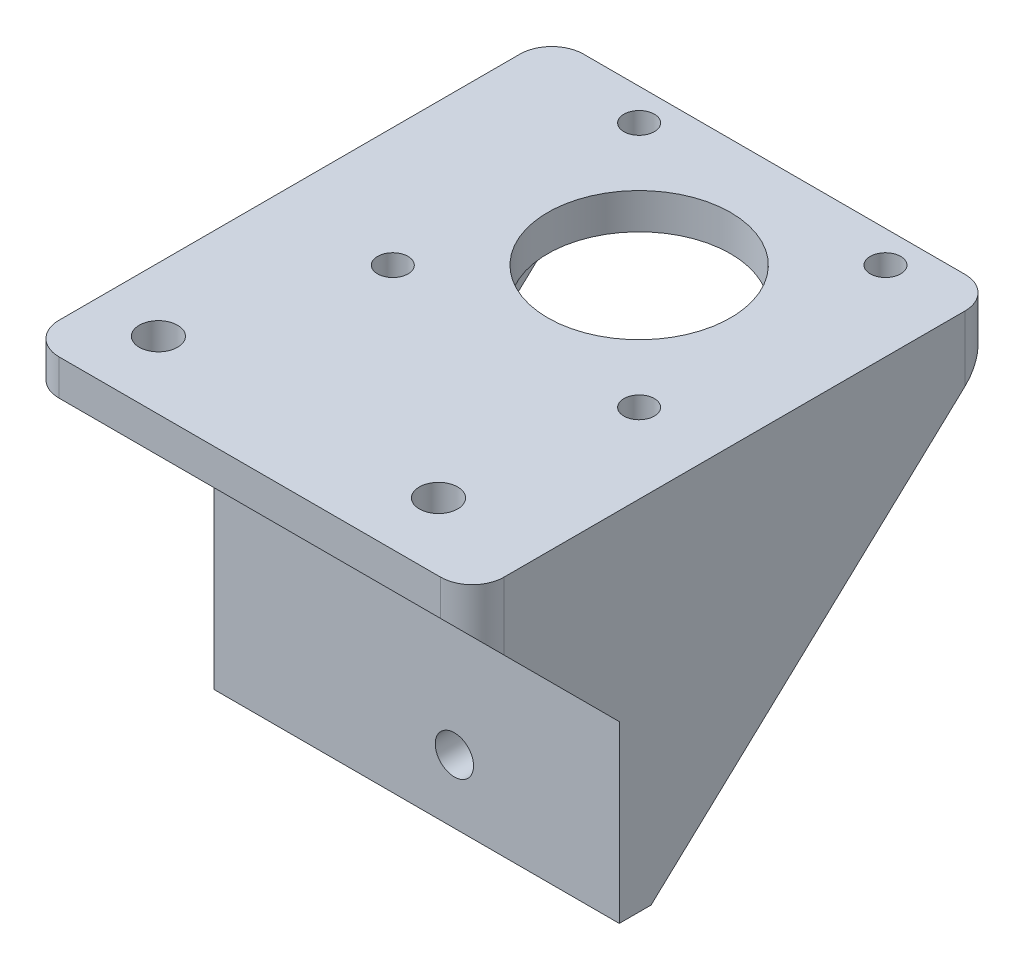
SolidWorks part; units mm, degrees
ref_plane "Front Plane" through (0, 0, 0) normal (0, 0, 1) x (1, 0, 0)
ref_plane "Top Plane" through (0, 0, 0) normal (0, 1, 0) x (1, 0, 0)
ref_plane "Right Plane" through (0, 0, 0) normal (1, 0, 0) x (0, 0, -1)
sketch "Sketch1" plane through (0, 0, 0) normal (0, 1, 0) x (1, 0, 0)
  line L0 (-15.5, 15.5) -> (15.5, -15.5) construction
  line L6 (15.5, 19.5) -> (-26.5, 19.5)
  line L7 (19.5, 15.5) -> (19.5, -42.5)
  line L8 (15.5, -46.5) -> (-26.5, -46.5)
  line L9 (-30.5, 15.5) -> (-30.5, -42.5)
  circle A0 centre (0, 0) radius 11.5
  circle A1 centre (15.5, 15.5) radius 1.9154
  circle A2 centre (-15.5, 15.5) radius 1.9154
  circle A3 centre (-15.5, -15.5) radius 1.9154
  circle A4 centre (15.5, -15.5) radius 1.9154
  arc A9 (-26.5, -46.5) -> (-30.5, -42.5) centre (-26.5, -42.5) cw
  arc A10 (19.5, -42.5) -> (15.5, -46.5) centre (15.5, -42.5) cw
  arc A11 (15.5, 19.5) -> (19.5, 15.5) centre (15.5, 15.5) cw
  arc A12 (-26.5, 19.5) -> (-30.5, 15.5) centre (-26.5, 15.5) ccw
  circle A13 centre (-22.5, -38) radius 2.41
  circle A14 centre (12.75, -38) radius 2.41
  point P15 (0, 0)
  point P37 (-30.5, -46.5)
  point P44 (-30.5, 19.5)
  dimension "D1" = 23
  dimension "D13" = 3.8309
  dimension "D14" = 4
  dimension "D10" = 4.82
  dimension "D2" = 31
  dimension "D3" = 31
  dimension "D4" = 50
  dimension "D5" = 66
  dimension "D6" = 4
  dimension "D7" = 4
  dimension "D8" = 8.5
  dimension "D9" = 8
  dimension "D11" = 6.75
extrude "Boss-Extrude1" add sketch "Sketch1" along normal blind 4.5
sketch "Sketch2" plane through (0, 0, 0) normal (0, 1, 0) x (1, 0, 0)
  line L0 (0, -2.475) -> (0, 2.475) construction
  line L1 (-21.5, -24) -> (21.5, -24)
  line L2 (-21.5, -24) -> (-21.5, 19)
  line L3 (-21.5, 19) -> (21.5, 19)
  line L4 (21.5, -24) -> (21.5, 19)
  line L5 (-21.5, -24) -> (21.5, 19) construction
  line L6 (-21.5, 19) -> (21.5, -24) construction
  line L7 (-25.5, -28) -> (25.5, -28)
  line L8 (-25.5, -28) -> (-25.5, 23)
  line L9 (-25.5, 23) -> (25.5, 23)
  line L10 (25.5, -28) -> (25.5, 23)
  line L11 (-25.5, -28) -> (25.5, 23) construction
  line L12 (-25.5, 23) -> (25.5, -28) construction
  point P0 (0, -2.5)
  point P6 (0, -2.5)
  point P14 (0, -2.5)
  point P15 (0, -2.5)
  dimension "D1" = 43
  dimension "D2" = 4
  dimension "D3" = 2.5
extrude "Boss-Extrude2" add sketch "Sketch2" against normal blind 40.5
sketch "Sketch3" plane through (0, 0, 0) normal (0, 1, 0) x (1, 0, 0)
  line L0 (-25.5, 19.5) -> (-25.5, 23)
  line L1 (-25.5, 23) -> (25.5, 23)
  line L2 (25.5, 23) -> (25.5, -28)
  line L3 (25.5, -28) -> (19.5, -28)
  line L4 (19.5, -28) -> (19.5, 15.5)
  line L5 (19.5, -42.5) -> (19.5, 15.5) construction
  line L6 (15.5, 19.5) -> (-25.5, 19.5)
  arc A0 (19.5, 15.5) -> (15.5, 19.5) centre (15.5, 15.5) ccw construction
  arc A1 (19.5, 15.5) -> (15.5, 19.5) centre (15.5, 15.5) ccw
extrude "Boss-Extrude3" add sketch "Sketch3" along normal up to surface (4.5 mm away) up to face at (-5.5, 4.5, 13.5)
sketch "Sketch4" plane through (0, 0, 0) normal (0, 1, 0) x (1, 0, 0)
  line L0 (25.5, 23) -> (25.5, -28) construction
  line L1 (-25.5, 23) -> (25.5, 23)
  line L2 (-25.5, 23) -> (-25.5, 19.5)
  line L3 (-25.5, 19.5) -> (25.5, 19.5)
  line L4 (25.5, 23) -> (25.5, 19.5)
  line L5 (-25.5, 19.5) -> (-26.5, 19.5) construction
extrude "Cut-Extrude1" cut sketch "Sketch4" against normal through all both and the other way through all
sketch "Sketch5" plane through (0, 0, 0) normal (1, 0, 0) x (0, 0, -1)
  line L0 (19.5, 0) -> (-24, -40.5)
  line L1 (55, 0) -> (-55, 0) construction
  line L2 (19.5, -40.5) -> (19.5, 4.5) construction
  line L3 (-24, -40.5) -> (19.5, -40.5)
  line L4 (19.5, -40.5) -> (19.5, 0)
extrude "Cut-Extrude2" cut sketch "Sketch5" against normal through all both and the other way through all
sketch "Sketch6" plane through (0, 0, 0) normal (0, 0, 1) x (1, 0, 0)
  line L0 (30.8, 0) -> (-30.8, 0) construction
  line L1 (-25.5, -40.5) -> (25.5, -40.5) construction
  line L2 (4.75, -10) -> (4.75, -32.5) construction
  circle A0 centre (4.75, -10) radius 2.412
  circle A1 centre (4.75, -32.5) radius 2.412
  circle A2 centre (0, 0) radius 6.75 construction
  circle A3 centre (-14.75, 0) radius 8 construction
  dimension "D3" = 4.824
  dimension "D5" = 16
  dimension "D6" = 13.5
  dimension "D1" = 10
  dimension "D2" = 8
  dimension "D4" = 19.5
extrude "Cut-Extrude3" cut sketch "Sketch6" against normal through all both and the other way through all
sketch "Sketch7" plane through (19.5, 0, 0) normal (1, 0, 0) x (0, 0, -1)
  line L0 (-46.5, 4.5) -> (-28, 4.5)
  line L1 (-28, 4.5) -> (-28, -18.5)
  line L2 (-28, -40.5) -> (-28, 4.5) construction
  line L3 (-28, -18.5) -> (-46.5, 0)
  line L5 (30.8, 0) -> (-30.8, 0) construction
  line L6 (-46.5, 4.5) -> (-46.5, 0)
  dimension "D1" = 45
extrude "Boss-Extrude4" add sketch "Sketch7" along normal up to surface and the other way up to surface
fillet "Fillet1" radius 4 2 edges at (25.5, 2.25, -19.5) (25.5, 2.25, 46.5)
sketch "Sketch8" plane through (0, 0, 0) normal (0, 1, 0) x (1, 0, 0)
  line L0 (-26.5, -46.5) -> (21.5, -46.5) construction
  line L1 (15.5, -46.5) -> (21.5, -46.5)
  line L2 (15.5, -46.5) -> (15.5, -28)
  line L3 (15.5, -28) -> (21.5, -28)
  line L4 (21.5, -46.5) -> (21.5, -28)
  line L5 (-25.5, -28) -> (25.5, -28) construction
  line L6 (21.5, -24) -> (21.5, 19) construction
extrude "Cut-Extrude4" cut sketch "Sketch8" against normal through all
ref_plane "Plane1" through (4.75, 0, 0) normal (1, 0, 0) x (0, 0, -1)
